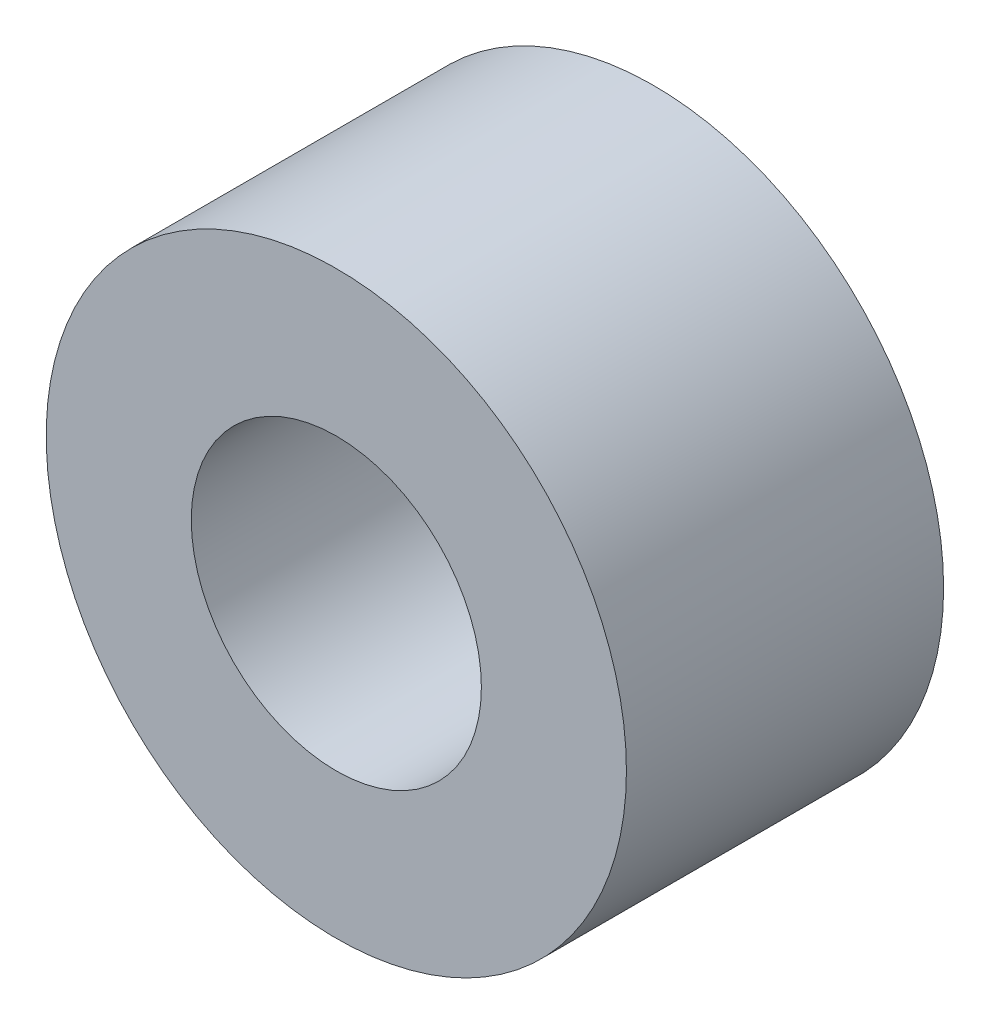
SolidWorks part; units mm, degrees
material "ABS"
ref_plane "Front Plane" through (0, 0, 0) normal (0, 0, 1) x (1, 0, 0)
ref_plane "Top Plane" through (0, 0, 0) normal (0, 1, 0) x (1, 0, 0)
ref_plane "Right Plane" through (0, 0, 0) normal (1, 0, 0) x (0, 0, -1)
sketch "Sketch1" plane through (0, 0, 0) normal (0, 0, 1) x (1, 0, 0)
  circle A0 centre (0, 0) radius 2.3813
  circle A1 centre (0, 0) radius 4.7625
  dimension "D1" = 4.7625
  dimension "D2" = 9.525
extrude "Boss-Extrude1" add sketch "Sketch1" along normal blind 5.207
